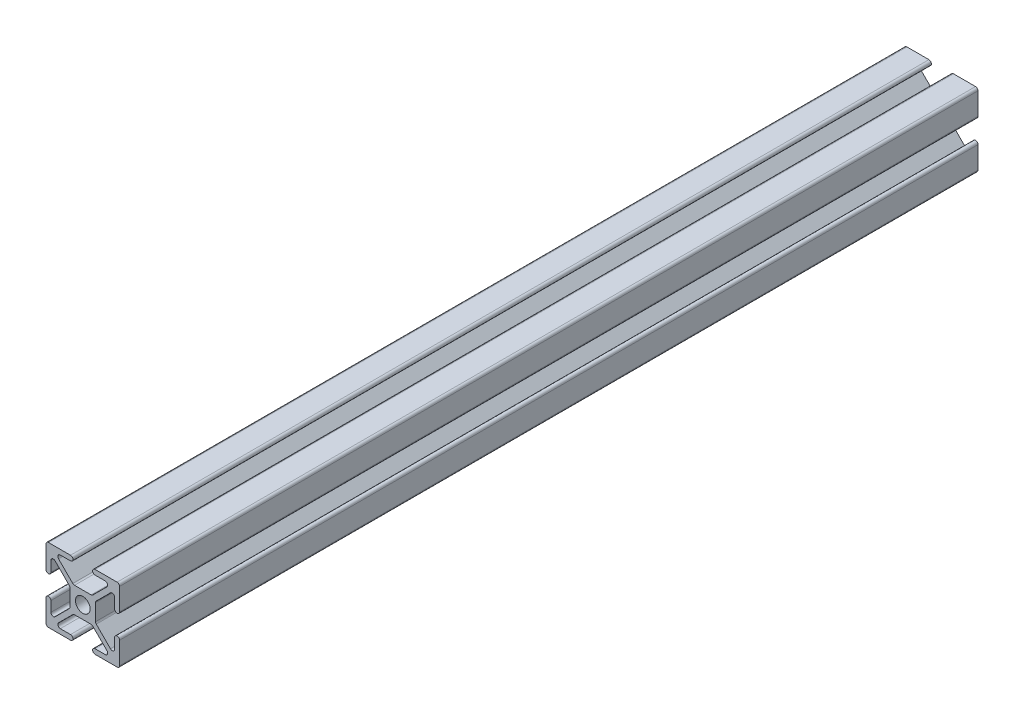
SolidWorks part; units mm, degrees
ref_plane "Alzado" through (0, 0, 0) normal (0, 0, 1) x (1, 0, 0)
ref_plane "Planta" through (0, 0, 0) normal (0, 1, 0) x (1, 0, 0)
ref_plane "Vista lateral" through (0, 0, 0) normal (1, 0, 0) x (0, 0, -1)
sketch "Croquis1" plane through (0, 0, 0) normal (0, 0, 1) x (1, 0, 0)
  line L1 (-14, 15) -> (14, 15)
  line L2 (-15, 14) -> (-15, -14)
  line L3 (-14, -15) -> (14, -15)
  line L4 (15, 14) -> (15, -14)
  line L5 (-15, 15) -> (15, -15) construction
  line L6 (-15, -15) -> (15, 15) construction
  arc A0 (-14, 15) -> (-15, 14) centre (-14, 14) ccw
  arc A1 (14, -15) -> (15, -14) centre (14, -14) ccw
  arc A2 (-14, -15) -> (-15, -14) centre (-14, -14) cw
  arc A3 (15, 14) -> (14, 15) centre (14, 14) ccw
  point P0 (0, 0)
  dimension "D3" = 1
  dimension "D4" = 1
  dimension "D1" = 30
  dimension "D2" = 30
extrude "Saliente-Extruir1" add sketch "Croquis1" against normal blind 350
sketch "Croquis2" plane through (0, 0, 0) normal (0, 0, 1) x (1, 0, 0)
  circle A0 centre (0, 0) radius 3
  dimension "D1" = 6
sketch "Croquis3" plane through (0, 0, 0) normal (0, 0, 1) x (1, 0, 0)
  line L0 (-15, 0) -> (15, 0) construction
  line L1 (4.0787, -5.4929) -> (9.8787, -11.2929)
  line L2 (-11.2929, 9.8787) -> (-5.4929, 4.0787)
  line L3 (-9.8787, 11.2929) -> (-4.0787, 5.4929)
  line L4 (-13, 9.1716) -> (-13, 5)
  line L5 (-15, 14) -> (-15, -14) construction
  line L6 (-5.2, 3.3716) -> (-5.2, -3.3716)
  line L7 (-9.1716, 13) -> (-5, 13)
  line L8 (9.8787, 11.2929) -> (4.0787, 5.4929)
  line L9 (11.2929, 9.8787) -> (5.4929, 4.0787)
  line L10 (-3.3716, 5.2) -> (3.3716, 5.2)
  line L11 (14, 15) -> (-14, 15) construction
  line L12 (13, 9.1716) -> (13, 5)
  line L13 (5.2, 3.3716) -> (5.2, -3.3716)
  line L14 (15, -14) -> (15, 14) construction
  line L15 (-9.1716, -13) -> (-5, -13)
  line L16 (-3.3716, -5.2) -> (3.3716, -5.2)
  line L17 (-14, -15) -> (14, -15) construction
  line L18 (-5.4929, -4.0787) -> (-11.2929, -9.8787)
  line L19 (5.4929, -4.0787) -> (11.2929, -9.8787)
  line L20 (-4.0787, -5.4929) -> (-9.8787, -11.2929)
  line L21 (5, -13) -> (9.1716, -13)
  line L22 (-13, -5) -> (-13, -9.1716)
  line L23 (13, -5) -> (13, -9.1716)
  line L24 (0, 15) -> (0, -5.2) construction
  line L34 (5, 13) -> (9.1716, 13)
  arc A0 (9.8787, 11.2929) -> (9.1716, 13) centre (9.1716, 12) ccw
  arc A1 (-9.8787, 11.2929) -> (-9.1716, 13) centre (-9.1716, 12) cw
  arc A2 (9.8787, 11.2929) -> (9.1716, 13) centre (9.1716, 12) ccw
  arc A3 (13, 9.1716) -> (11.2929, 9.8787) centre (12, 9.1716) ccw
  arc A4 (11.2929, -9.8787) -> (13, -9.1716) centre (12, -9.1716) ccw
  arc A5 (9.1716, -13) -> (9.8787, -11.2929) centre (9.1716, -12) ccw
  arc A6 (-9.1716, -13) -> (-9.8787, -11.2929) centre (-9.1716, -12) cw
  arc A7 (-11.2929, -9.8787) -> (-13, -9.1716) centre (-12, -9.1716) cw
  arc A8 (-13, 9.1716) -> (-11.2929, 9.8787) centre (-12, 9.1716) cw
  arc A9 (-4.0787, -5.4929) -> (-3.3716, -5.2) centre (-3.3716, -6.2) cw
  arc A10 (3.3716, -5.2) -> (4.0787, -5.4929) centre (3.3716, -6.2) cw
  arc A11 (5.4929, -4.0787) -> (5.2, -3.3716) centre (6.2, -3.3716) cw
  arc A12 (5.2, 3.3716) -> (5.4929, 4.0787) centre (6.2, 3.3716) cw
  arc A13 (3.3716, 5.2) -> (4.0787, 5.4929) centre (3.3716, 6.2) ccw
  arc A14 (-3.3716, 5.2) -> (-4.0787, 5.4929) centre (-3.3716, 6.2) cw
  arc A15 (-5.4929, -4.0787) -> (-5.2, -3.3716) centre (-6.2, -3.3716) ccw
  arc A16 (-5.2, 3.3716) -> (-5.4929, 4.0787) centre (-6.2, 3.3716) ccw
  circle A17 centre (-14, -5) radius 1
  circle A18 centre (-14, 5) radius 1
  circle A19 centre (-5, -14) radius 1
  circle A20 centre (5, -14) radius 1
  circle A21 centre (14, 5) radius 1
  circle A22 centre (14, -5) radius 1
  circle A23 centre (-5, 14) radius 1
  circle A24 centre (5, 14) radius 1
  point P20 (-11.5858, -13)
  point P30 (-13, -11.5858)
  point P43 (-3.7858, -5.2)
  point P50 (3.7858, -5.2)
  point P53 (5.2, -3.7858)
  point P62 (-5.2, -3.7858)
  line M2 (-15, 14) -> (-15, -14)
  line M4 (-14, -15) -> (14, -15)
  line M6 (15, -14) -> (15, 14)
  line M8 (14, 15) -> (-14, 15)
  dimension "D6" = 9.8
  dimension "D7" = 2
  dimension "D12" = 2
  dimension "D19" = 1
  dimension "D2" = 1
  dimension "D3" = 1
  dimension "D4" = 1
  dimension "D16" = 1
  dimension "D5" = 2
  dimension "D8" = 9.8
  dimension "D9" = 2
  dimension "D10" = 9.8
  dimension "D11" = 9.8
  dimension "D15" = 1
  dimension "D20" = 1
  dimension "D23" = 1
  dimension "D24" = 1
  dimension "D27" = 1
  dimension "D28" = 1
extrude "Cortar-Extruir1" cut sketch "Croquis2" against normal through all
extrude "Cortar-Extruir3" cut sketch "Croquis3" against normal through all contours A18 A17 L22 A7 L18 A15 L6 A16 L2 A8 L4 M2 | A24 A23 L7 A1 L3 A14 L10 A13 L8 A0 L34 M8 | A20 L21 A5 L1 A10 L16 A9 L20 A6 L15 A19 M4 | A22 A21 L12 A3 L9 A12 L13 A11 L19 A4 L23 M6
